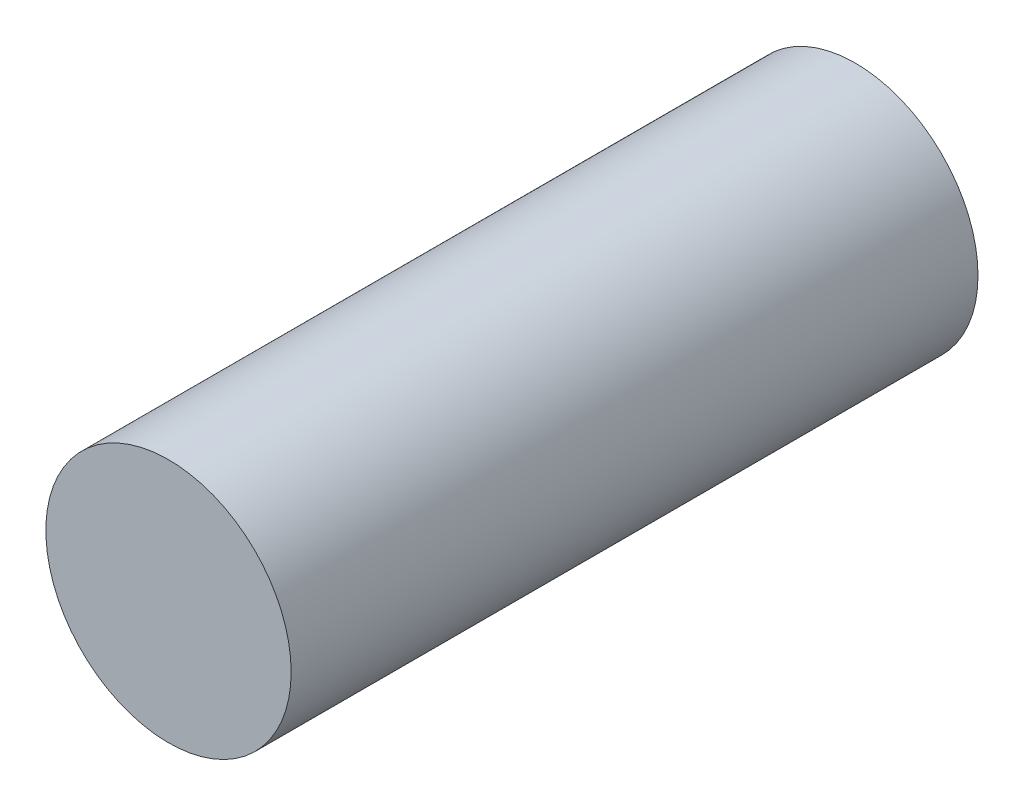
SolidWorks part; units mm, degrees
ref_plane "Front Plane" through (0, 0, 0) normal (0, 0, 1) x (1, 0, 0)
ref_plane "Top Plane" through (0, 0, 0) normal (0, 1, 0) x (1, 0, 0)
ref_plane "Right Plane" through (0, 0, 0) normal (1, 0, 0) x (0, 0, -1)
sketch "Sketch1" plane through (0, 0, 0) normal (0, 0, 1) x (1, 0, 0)
  circle A0 centre (0, 0) radius 2.5
  dimension "D1" = 5
extrude "Boss-Extrude1" add sketch "Sketch1" along normal blind 14
ref_point "Centre"
